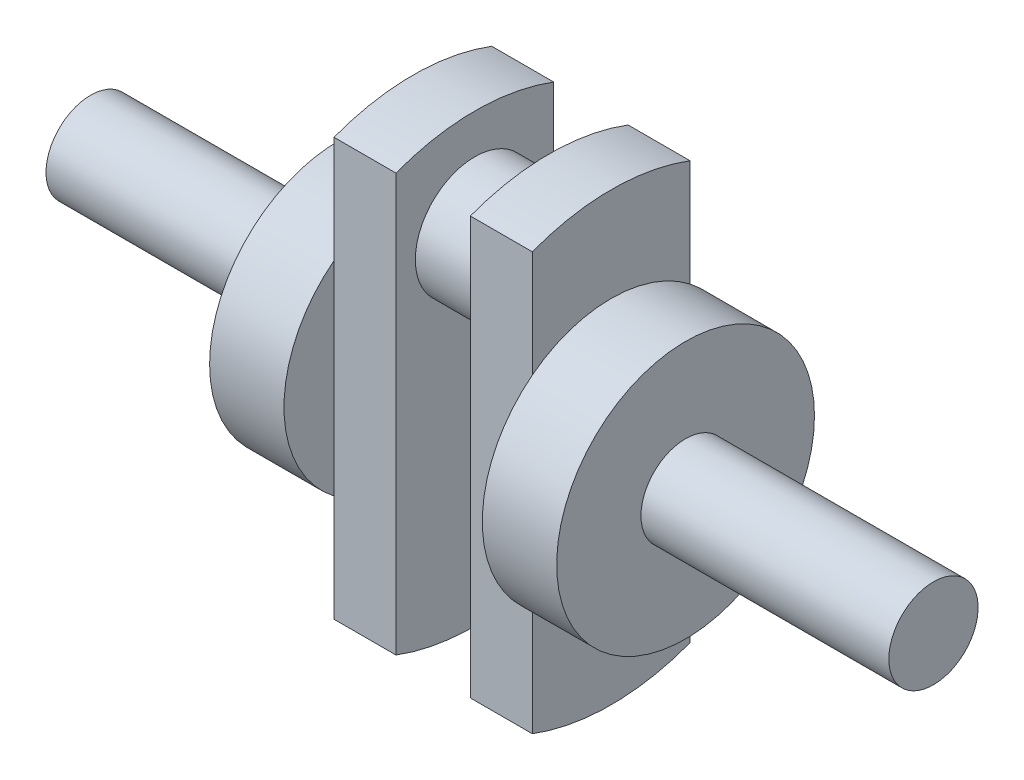
SolidWorks part; units mm, degrees
ref_plane "Front Plane" through (0, 0, 0) normal (0, 0, 1) x (1, 0, 0)
ref_plane "Top Plane" through (0, 0, 0) normal (0, 1, 0) x (1, 0, 0)
ref_plane "Right Plane" through (0, 0, 0) normal (1, 0, 0) x (0, 0, -1)
sketch "Sketch1" plane through (0, 0, 0) normal (1, 0, 0) x (0, 0, -1)
  line L2 (-15.9066, -42.0949) -> (-15.9066, 42.0949)
  line L4 (15.9066, -42.0949) -> (15.9066, 42.0949)
  line L5 (-20, -67.5594) -> (20, 67.5594) construction
  line L6 (-20, 67.5594) -> (20, -67.5594) construction
  arc A0 (-15.9066, -42.0949) -> (15.9066, -42.0949) centre (0, 0) ccw
  arc A1 (15.9066, 42.0949) -> (-15.9066, 42.0949) centre (0, 0) ccw
  dimension "D1" = 40
extrude "Boss-Extrude1" add sketch "Sketch1" along normal blind 40
sketch "Sketch2" plane through (0, 0, 0) normal (-1, 0, 0) x (0, 0, 1)
  circle A0 centre (0, 0) radius 9
extrude "Boss-Extrude2" add sketch "Sketch2" along normal blind 65 and the other way blind 105
sketch "Sketch3" plane through (0, 0, 15.9066) normal (0, 0, 1) x (1, 0, 0)
  line L1 (12.5, 65.7291) -> (27.5, 65.7291)
  line L2 (12.5, 65.7291) -> (12.5, -64.2709)
  line L3 (12.5, -64.2709) -> (27.5, -64.2709)
  line L4 (27.5, 65.7291) -> (27.5, -64.2709)
  dimension "D1" = 15
  dimension "D2" = 12.5
  dimension "D3" = 130
extrude "Cut-Extrude1" cut sketch "Sketch3" against normal up to surface (31.8133 mm away) up to face at (20, 0, -15.9066)
sketch "Sketch4" plane through (40, 0, 0) normal (1, 0, 0) x (0, 0, -1)
  circle A0 centre (0, 25) radius 12
  arc A1 (15.9066, 42.0949) -> (-15.9066, 42.0949) centre (0, 0) ccw construction
  arc A2 (-15.9066, -42.0949) -> (15.9066, -42.0949) centre (0, 0) ccw construction
  arc A3 (15.9066, 42.0949) -> (-15.9066, 42.0949) centre (0, 0) ccw construction
  dimension "D1" = 25
extrude "Boss-Extrude3" add sketch "Sketch4" against normal up to surface (40 mm away) up to face at (0, 0, -9)
sketch "Sketch5" plane through (0, 0, 0) normal (-1, 0, 0) x (0, 0, 1)
  circle A0 centre (0, 0) radius 26
extrude "Boss-Extrude4" add sketch "Sketch5" along normal blind 15
sketch "Sketch6" plane through (40, 0, 0) normal (1, 0, 0) x (0, 0, -1)
  circle A0 centre (0, 0) radius 26
extrude "Boss-Extrude5" add sketch "Sketch6" along normal blind 15
